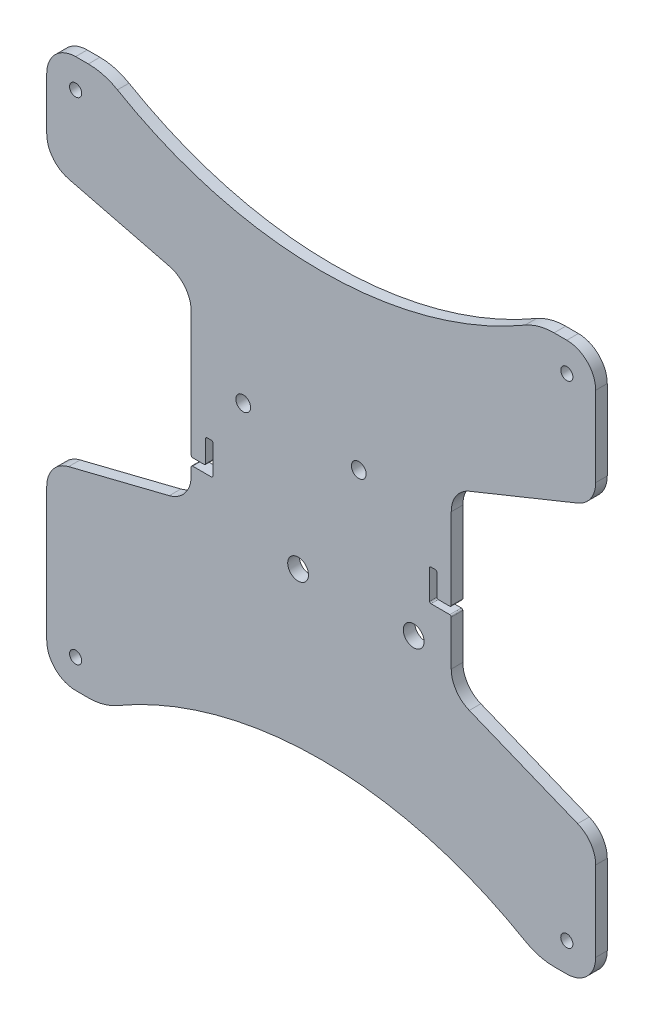
SolidWorks part; units mm, degrees
ref_plane "Front Plane" through (0, 0, 0) normal (0, 0, 1) x (1, 0, 0)
ref_plane "Top Plane" through (0, 0, 0) normal (0, 1, 0) x (1, 0, 0)
ref_plane "Right Plane" through (0, 0, 0) normal (1, 0, 0) x (0, 0, -1)
ref_plane "Plane1" through (0, 0, 4) normal (0, 0, 1) x (1, 0, 0)
sketch "Sketch1" plane through (0, 0, 4) normal (0, 0, 1) x (1, 0, 0)
  line L0 (-45, -8) -> (-45, -10.6922)
  line L1 (-52.5746, -20.3937) -> (-87.4254, -29.1063)
  line L2 (-95, -38.8078) -> (-95, -85)
  line L3 (-85, -95) -> (-80.6, -95)
  line L4 (80.6, -95) -> (85, -95)
  line L5 (95, -85) -> (95, -57.3099)
  line L6 (88.7544, -48.0415) -> (51.2456, -32.8477)
  line L7 (45, -23.5792) -> (45, -8)
  line L8 (44.5, -7.5) -> (38, -7.5)
  line L9 (37.5, -7) -> (37.5, 3)
  line L10 (38, 3.5) -> (39.5, 3.5)
  line L11 (40, 3) -> (40, -4.5)
  line L12 (40.5, -5) -> (44.5, -5)
  line L13 (45, -4.5) -> (45, 23.5792)
  line L14 (51.2456, 32.8477) -> (88.7544, 48.0415)
  line L15 (95, 57.3099) -> (95, 85)
  line L16 (85, 95) -> (80.6, 95)
  line L17 (-80.6, 95) -> (-85, 95)
  line L18 (-95, 85) -> (-95, 66.8078)
  line L19 (-87.4254, 57.1063) -> (-52.5746, 48.3937)
  line L20 (-45, 38.6922) -> (-45, -4.5)
  line L21 (-44.5, -5) -> (-40.5, -5)
  line L22 (-40, -4.5) -> (-40, 3)
  line L23 (-39.5, 3.5) -> (-38, 3.5)
  line L24 (-37.5, 3) -> (-37.5, -7)
  line L25 (-38, -7.5) -> (-44.5, -7.5)
  circle A0 centre (13, 20.1) radius 2.55
  circle A1 centre (32, -20.1) radius 3.6
  circle A2 centre (-8, -20.1) radius 3.6
  circle A3 centre (-27, 20.1) radius 2.55
  arc A4 (-45, -10.6922) -> (-52.5746, -20.3937) centre (-55, -10.6922) cw
  arc A5 (-87.4254, -29.1063) -> (-95, -38.8078) centre (-85, -38.8078) ccw
  arc A6 (-95, -85) -> (-85, -95) centre (-85, -85) ccw
  arc A7 (-80.6, -95) -> (-70.525, -92.277) centre (-80.6, -75) ccw
  arc A8 (-70.525, -92.277) -> (70.525, -92.277) centre (0, -213.2159) cw
  arc A9 (70.525, -92.277) -> (80.6, -95) centre (80.6, -75) ccw
  arc A10 (85, -95) -> (95, -85) centre (85, -85) ccw
  arc A11 (95, -57.3099) -> (88.7544, -48.0415) centre (85, -57.3099) ccw
  arc A12 (51.2456, -32.8477) -> (45, -23.5792) centre (55, -23.5792) cw
  arc A13 (45, -8) -> (44.5, -7.5) centre (44.5, -8) ccw
  arc A14 (38, -7.5) -> (37.5, -7) centre (38, -7) cw
  arc A15 (37.5, 3) -> (38, 3.5) centre (38, 3) cw
  arc A16 (39.5, 3.5) -> (40, 3) centre (39.5, 3) cw
  arc A17 (40, -4.5) -> (40.5, -5) centre (40.5, -4.5) ccw
  arc A18 (44.5, -5) -> (45, -4.5) centre (44.5, -4.5) ccw
  arc A19 (45, 23.5792) -> (51.2456, 32.8477) centre (55, 23.5792) cw
  arc A20 (88.7544, 48.0415) -> (95, 57.3099) centre (85, 57.3099) ccw
  arc A21 (95, 85) -> (85, 95) centre (85, 85) ccw
  arc A22 (80.6, 95) -> (70.525, 92.277) centre (80.6, 75) ccw
  arc A23 (70.525, 92.277) -> (-70.525, 92.277) centre (0, 213.2159) cw
  arc A24 (-70.525, 92.277) -> (-80.6, 95) centre (-80.6, 75) ccw
  arc A25 (-85, 95) -> (-95, 85) centre (-85, 85) ccw
  arc A26 (-95, 66.8078) -> (-87.4254, 57.1063) centre (-85, 66.8078) ccw
  arc A27 (-52.5746, 48.3937) -> (-45, 38.6922) centre (-55, 38.6922) cw
  arc A28 (-45, -4.5) -> (-44.5, -5) centre (-44.5, -4.5) ccw
  arc A29 (-40.5, -5) -> (-40, -4.5) centre (-40.5, -4.5) ccw
  arc A30 (-40, 3) -> (-39.5, 3.5) centre (-39.5, 3) cw
  arc A31 (-38, 3.5) -> (-37.5, 3) centre (-38, 3) cw
  arc A32 (-37.5, -7) -> (-38, -7.5) centre (-38, -7) cw
  arc A33 (-44.5, -7.5) -> (-45, -8) centre (-44.5, -8) ccw
  circle A34 centre (-85, 85) radius 2.1
  circle A35 centre (85, 85) radius 2.1
  circle A36 centre (-85, -85) radius 2.1
  circle A37 centre (85, -85) radius 2.1
extrude "Boss-Extrude1" add sketch "Sketch1" against normal blind 4
